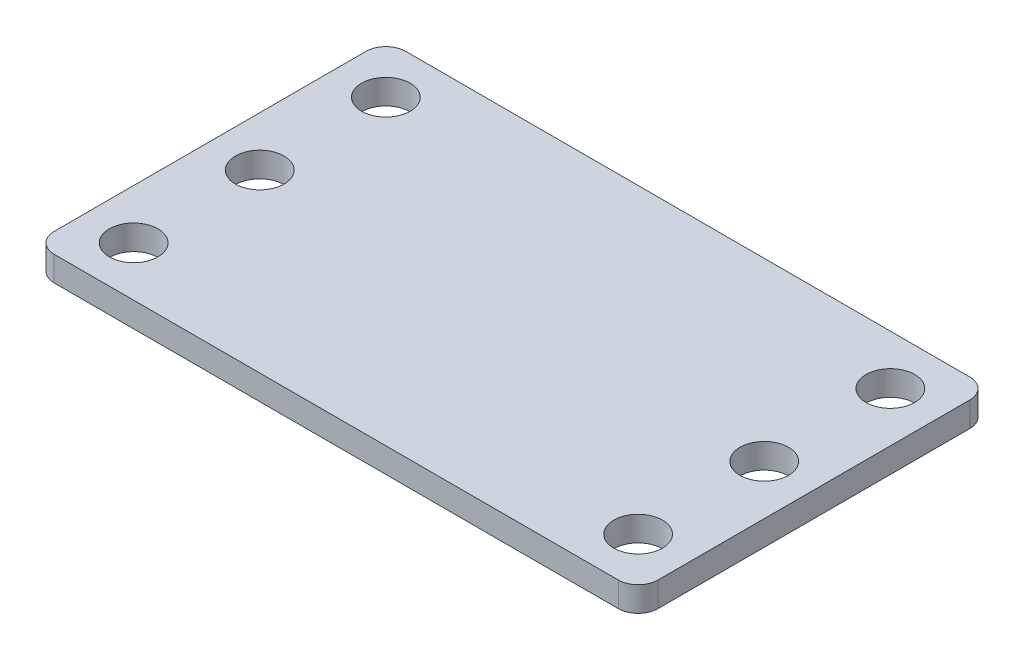
SolidWorks part; units mm, degrees
ref_plane "Front Plane" through (0, 0, 0) normal (0, 0, 1) x (1, 0, 0)
ref_plane "Top Plane" through (0, 0, 0) normal (0, 1, 0) x (1, 0, 0)
ref_plane "Right Plane" through (0, 0, 0) normal (1, 0, 0) x (0, 0, -1)
sketch "Croquis1" plane through (0, 0, 0) normal (0, 1, 0) x (1, 0, 0)
  line L0 (0, 0) -> (0, 17.113) construction
  line L1 (-25.4, 12.7) -> (25.4, 12.7) construction
  line L2 (-25.4, 12.7) -> (-25.4, -12.7) construction
  line L3 (-25.4, -12.7) -> (25.4, -12.7) construction
  line L4 (25.4, 12.7) -> (25.4, -12.7) construction
  line L5 (-25.4, 12.7) -> (25.4, -12.7) construction
  line L6 (-25.4, -12.7) -> (25.4, 12.7) construction
  line L8 (-30.4, 17.7) -> (30.4, 17.7)
  line L9 (-30.4, 17.7) -> (-30.4, -17.7)
  line L10 (-30.4, -17.7) -> (30.4, -17.7)
  line L11 (30.4, 17.7) -> (30.4, -17.7)
  line L12 (-30.4, 17.7) -> (30.4, -17.7) construction
  line L13 (-30.4, -17.7) -> (30.4, 17.7) construction
  circle A0 centre (-25.4, 12.7) radius 2.45
  circle A1 centre (-25.4, 0) radius 2.45
  circle A2 centre (-25.4, -12.7) radius 2.45
  circle A3 centre (25.4, -12.7) radius 2.45
  circle A4 centre (25.4, 0) radius 2.45
  circle A5 centre (25.4, 12.7) radius 2.45
  point P0 (0, 0)
  dimension "D3" = 4.9
  dimension "D1" = 50.8
  dimension "D2" = 25.4
  dimension "D4" = 5
  dimension "D5" = 5
extrude "Saliente-Extruir1" add sketch "Croquis1" along normal blind 2.5
fillet "Redondeo1" radius 2 4 edges at (-30.4, 1.25, -17.7) (30.4, 1.25, -17.7) (30.4, 1.25, 17.7) (-30.4, 1.25, 17.7)
